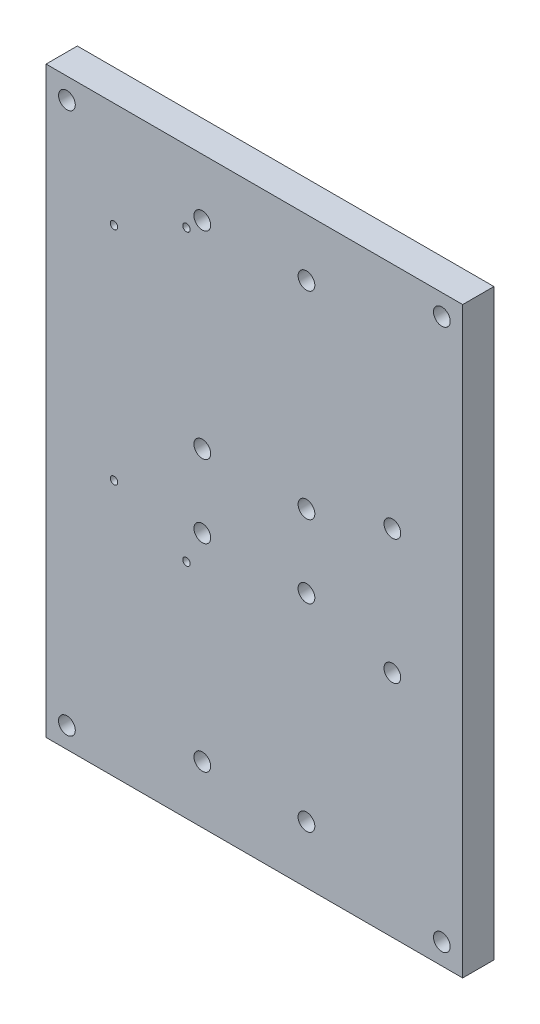
SolidWorks part; units mm, degrees
material "6061 Alloy"
ref_plane "Front Plane" through (0, 0, 0) normal (0, 0, 1) x (1, 0, 0)
ref_plane "Top Plane" through (0, 0, 0) normal (0, 1, 0) x (1, 0, 0)
ref_plane "Right Plane" through (0, 0, 0) normal (1, 0, 0) x (0, 0, -1)
sketch "Sketch1" plane through (0, 0, 0) normal (0, 0, 1) x (1, 0, 0)
  line L1 (-63.5, 88.9) -> (63.5, 88.9)
  line L2 (-63.5, 88.9) -> (-63.5, -88.9)
  line L3 (-63.5, -88.9) -> (63.5, -88.9)
  line L4 (63.5, 88.9) -> (63.5, -88.9)
  line L5 (-63.5, 88.9) -> (63.5, -88.9) construction
  line L6 (-63.5, -88.9) -> (63.5, 88.9) construction
  point P0 (0, 0)
  dimension "D1" = 127
  dimension "D2" = 177.8
extrude "Boss-Extrude1" add sketch "Sketch1" along normal mid plane 9.525 contours L1 L4 L3 L2
hole_wizard "#10 Clearance Hole1" positions "Sketch3" profile "Sketch2" hole size "#10" standard "ANSI Inch" end condition through all
sketch "Sketch3" plane through (0, 0, -4.7625) normal (0, 0, -1) x (-1, 0, 0)
  line L14 (-63.5, 82.55) -> (63.5, 82.55) construction
  line L15 (-63.5, 88.9) -> (-63.5, -88.9) construction
  line L16 (63.5, 88.9) -> (63.5, -88.9) construction
  line L18 (-63.5, -82.55) -> (63.5, -82.55) construction
  line L20 (63.5, 88.9) -> (-63.5, 88.9) construction
  line L21 (63.5, -88.9) -> (-63.5, -88.9) construction
  point P562 (-57.15, 82.55)
  point P566 (57.15, 82.55)
  point P568 (57.15, -82.55)
  point P572 (-57.15, -82.55)
  dimension "D1" = 6.35
  dimension "D2" = 6.35
  dimension "D3" = 6.35
  dimension "D4" = 6.35
sketch "Sketch2" plane through (57.15, 82.55, -4.7625) normal (1, 0, 0) x (0, 1, 0)
  line L0 (0, 0) -> (0, 9.525)
  line L1 (0, 9.525) -> (2.5527, 9.525)
  line L2 (2.5527, 9.525) -> (2.5527, 0)
  line L5 (2.5527, 0) -> (0, 0)
  line L11 (0, -6.35) -> (0, 107.95) construction
  dimension "Thru Hole Dia." = 5.1054
  dimension "Thru Hole Depth" = 9.525
hole_wizard "Tapped Hole for #10-32 Helicoil1" positions "Sketch5" profile "Sketch4" tap size "#10-32" standard "Helicoil® Inch"
sketch "Sketch5" plane through (0, 0, -4.7625) normal (0, 0, -1) x (-1, 0, 0)
  line L1 (-15.875, 71.4375) -> (15.875, 71.4375) construction
  line L2 (-15.875, 71.4375) -> (-15.875, 11.1125) construction
  line L3 (-15.875, 11.1125) -> (15.875, 11.1125) construction
  line L4 (15.875, 71.4375) -> (15.875, 11.1125) construction
  line L5 (63.5, 88.9) -> (63.5, -88.9) construction
  line L6 (63.5, 88.9) -> (-63.5, 88.9) construction
  line L7 (0, 11.1125) -> (0, -11.1125) construction
  line L10 (-15.875, -11.1125) -> (15.875, -11.1125) construction
  line L11 (-15.875, -11.1125) -> (-15.875, -71.4375) construction
  line L12 (-15.875, -71.4375) -> (15.875, -71.4375) construction
  line L13 (15.875, -11.1125) -> (15.875, -71.4375) construction
  line L14 (0, 0) -> (63.5, 0) construction
  point P1 (-15.875, 71.4375)
  point P2 (15.875, 11.1125)
  point P61 (-15.875, 11.1125)
  point P62 (15.875, 71.4375)
  point P81 (-15.875, -11.1125)
  point P82 (15.875, -71.4375)
  point P253 (-15.875, -71.4375)
  point P254 (15.875, -11.1125)
  dimension "D1" = 31.75
  dimension "D2" = 60.325
  dimension "D3" = 47.625
  dimension "D4" = 17.4625
  dimension "D5" = 22.225
sketch "Sketch4" plane through (15.875, 71.4375, -4.7625) normal (1, 0, 0) x (0, 1, 0)
  line L0 (0, 0) -> (0, 11.0578)
  line L1 (0, 11.0578) -> (2.5527, 9.524)
  line L2 (2.5527, 9.524) -> (2.5527, 0)
  line L5 (2.5527, 0) -> (0, 0)
  line L10 (0, 11.0578) -> (-2.5527, 9.524) construction
  line L11 (0, -6.35) -> (0, 107.95) construction
  dimension "Tap Drill Dia." = 5.1054
  dimension "Tap Drill Depth" = 9.524
  dimension "Drill Angle" = 118
hole_wizard "Tapped Hole for #10-32 Helicoil2" positions "Sketch7" profile "Sketch6" tap size "#10-32" standard "Helicoil® Inch"
sketch "Sketch7" plane through (0, 0, -4.7625) normal (0, 0, -1) x (-1, 0, 0)
  line L0 (-42.0688, 19.05) -> (-42.0688, -19.05) construction
  line L1 (-42.0687, 0) -> (0, 0) construction
  line L3 (63.5, 88.9) -> (-63.5, 88.9) construction
  line L4 (-63.5, 88.9) -> (-63.5, -88.9) construction
  point P1 (-42.0688, 19.05)
  point P2 (-42.0688, -19.05)
  dimension "D1" = 69.85
  dimension "D2" = 21.4312
sketch "Sketch6" plane through (42.0688, 19.05, -4.7625) normal (1, 0, 0) x (0, 1, 0)
  line L0 (0, 0) -> (0, 11.0578)
  line L1 (0, 11.0578) -> (2.5527, 9.524)
  line L2 (2.5527, 9.524) -> (2.5527, 0)
  line L5 (2.5527, 0) -> (0, 0)
  line L10 (0, 11.0578) -> (-2.5527, 9.524) construction
  line L11 (0, -6.35) -> (0, 107.95) construction
  dimension "Tap Drill Dia." = 5.1054
  dimension "Tap Drill Depth" = 9.524
  dimension "Drill Angle" = 118
hole_wizard "#4-40 Tapped Hole1" positions "Sketch9" profile "Sketch8" tap size "#4-40" standard "ANSI Inch" end condition through all
sketch "Sketch9" plane through (0, 0, 4.7625) normal (0, 0, 1) x (1, 0, 0)
  line L0 (-63.5, 61.9125) -> (-31.75, 61.9125) construction
  line L1 (-63.5, 88.9) -> (-63.5, -88.9) construction
  line L3 (-63.5, -15.875) -> (-31.75, -15.875) construction
  line L5 (-20.701, 67.1195) -> (-42.799, 56.7055) construction
  line L7 (-20.701, -21.082) -> (-42.799, -10.668) construction
  line L8 (-63.5, 88.9) -> (63.5, 88.9) construction
  point P11 (-20.701, 67.1195)
  point P12 (-42.799, 56.7055)
  point P15 (-20.701, -21.082)
  point P16 (-42.799, -10.668)
  dimension "D1" = 22.098
  dimension "D2" = 10.414
  dimension "D3" = 26.9875
  dimension "D4" = 31.75
  dimension "D5" = 22.098
  dimension "D6" = 10.414
  dimension "D7" = 77.7875
sketch "Sketch8" plane through (-20.701, 67.1195, 4.7625) normal (1, 0, 0) x (0, -1, 0)
  line L0 (0, 0) -> (0, 9.525)
  line L1 (0, 9.525) -> (1.1303, 9.525)
  line L2 (1.1303, 9.525) -> (1.1303, 0)
  line L5 (1.1303, 0) -> (0, 0)
  line L11 (0, -6.35) -> (0, 107.95) construction
  dimension "Thread Major Dia." = 2.2606
  dimension "Thru Tap Drill Depth" = 9.525
chamfer "Chamfer1" [suppressed] distance 0.508 angle 45
